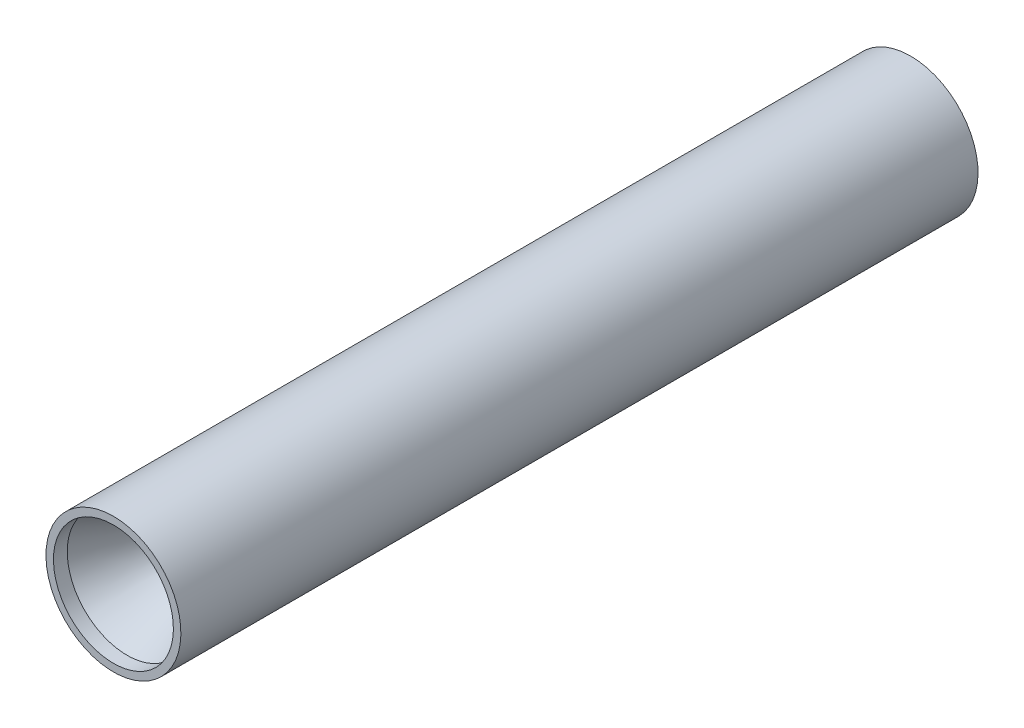
SolidWorks part; units mm, degrees
material "6061-T6 (SS)"
ref_plane "Front Plane" through (0, 0, 0) normal (0, 0, 1) x (1, 0, 0)
ref_plane "Top Plane" through (0, 0, 0) normal (0, 1, 0) x (1, 0, 0)
ref_plane "Right Plane" through (0, 0, 0) normal (1, 0, 0) x (0, 0, -1)
sketch "Sketch1" plane through (0, 0, 0) normal (1, 0, 0) x (0, 0, -1)
  line L0 (-289.5, 49) -> (289.5, 49)
  line L1 (289.5, 49) -> (289.5, 10)
  line L2 (289.5, 10) -> (279.5, 10)
  line L3 (279.5, 10) -> (279.5, 0)
  line L4 (279.5, 0) -> (264.5, 0)
  line L5 (264.5, 0) -> (264.5, 35.25)
  line L6 (264.5, 35.25) -> (-169.5, 35.25)
  line L7 (-169.5, 35.25) -> (-169.5, 39)
  line L8 (-169.5, 39) -> (-179.5, 39)
  line L9 (-179.5, 39) -> (-204.5, 14)
  line L10 (-219.5, 15.5766) -> (-204.5, 14)
  line L11 (-219.5, 15.5766) -> (-279.5, 43.555)
  line L12 (-279.5, 43.555) -> (-289.5, 43.555)
  line L13 (-289.5, 43.555) -> (-289.5, 49)
  line L14 (279.5, 0) -> (-433.5179, 0) construction
  point P7 (272, 0)
  dimension "D1" = 579
  dimension "D2" = 49
  dimension "D3" = 10
  dimension "D4" = 6
  dimension "D5" = 25
  dimension "D6" = 60
  dimension "D7" = 25
  dimension "D8" = 10
  dimension "D9" = 135
  dimension "D10" = 35
  dimension "D11" = 10
  dimension "D12" = 13.75
  dimension "D13" = 35
  dimension "D14" = 15
  dimension "D15" = 10
  dimension "D16" = 289.5
revolve "Revolve1" add sketch "Sketch1" angle 360 about L14
